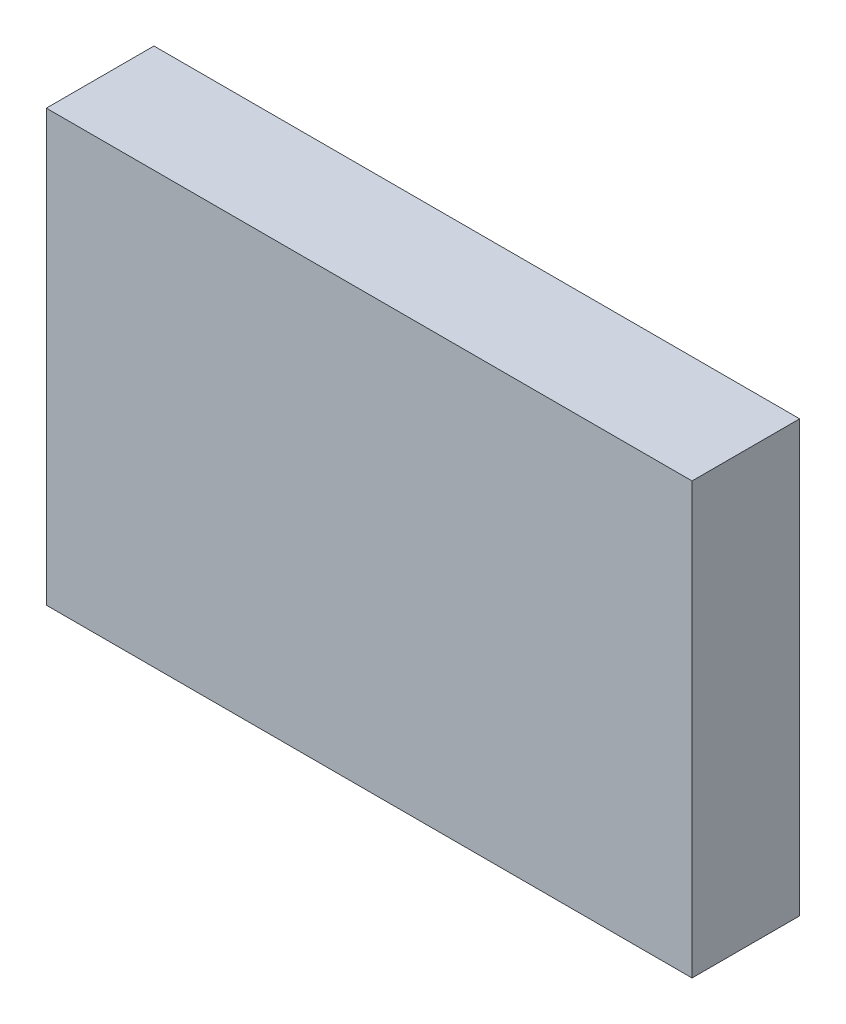
SolidWorks part; units mm, degrees
ref_plane "前视基准面" through (0, 0, 0) normal (0, 0, 1) x (1, 0, 0)
ref_plane "上视基准面" through (0, 0, 0) normal (0, 1, 0) x (1, 0, 0)
ref_plane "右视基准面" through (0, 0, 0) normal (1, 0, 0) x (0, 0, -1)
sketch "草图1" plane through (0, 0, 0) normal (0, 0, 1) x (1, 0, 0)
  line L1 (-45, 62.7661) -> (45, 62.7661)
  line L2 (-45, 62.7661) -> (-45, 2.7661)
  line L3 (-45, 2.7661) -> (45, 2.7661)
  line L4 (45, 62.7661) -> (45, 2.7661)
  line L5 (-45, 62.7661) -> (45, 2.7661) construction
  line L6 (-45, 2.7661) -> (45, 62.7661) construction
  point P0 (0, 32.7661)
  dimension "D1" = 90
  dimension "D2" = 60
extrude "凸台-拉伸1" add sketch "草图1" along normal blind 15
